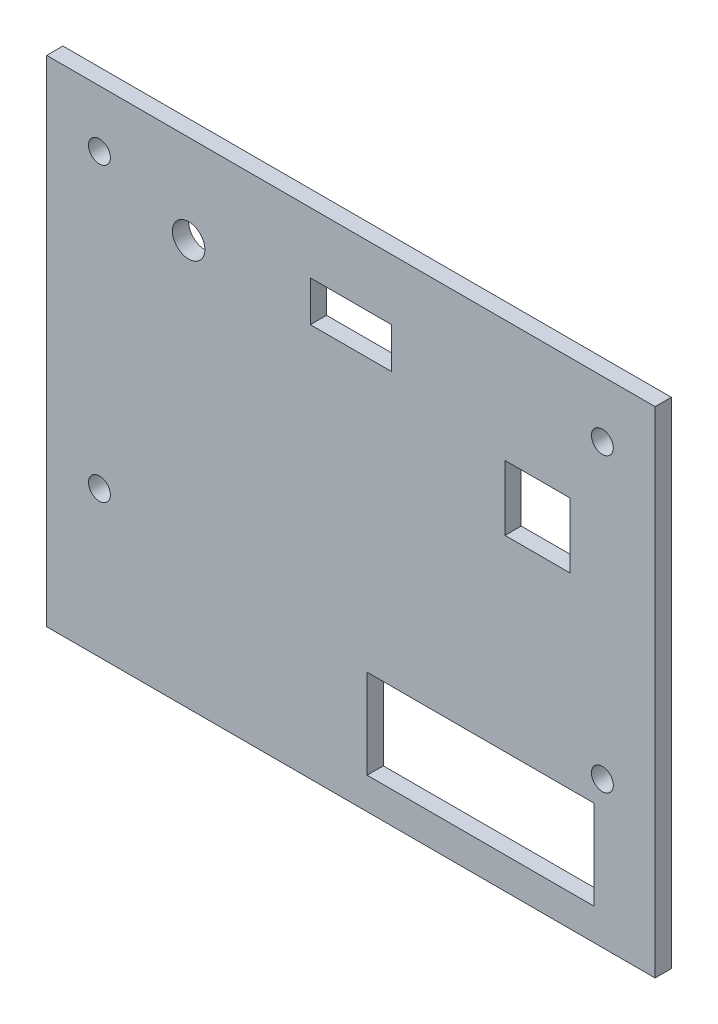
SolidWorks part; units mm, degrees
ref_plane "前视基准面" through (0, 0, 0) normal (0, 0, 1) x (1, 0, 0)
ref_plane "上视基准面" through (0, 0, 0) normal (0, 1, 0) x (1, 0, 0)
ref_plane "右视基准面" through (0, 0, 0) normal (1, 0, 0) x (0, 0, -1)
other "Configuration Table"
sketch "草图1" plane through (0, 0, 0) normal (0, 0, 1) x (1, 0, 0)
  line L1 (0, 0) -> (75, 0)
  line L2 (0, 0) -> (0, 61)
  line L3 (0, 61) -> (75, 61)
  line L4 (75, 0) -> (75, 61)
extrude "凸台-拉伸1" add sketch "草图1" along normal blind 2
sketch "草图2" plane through (0, 0, 0) normal (0, 0, 1) x (1, 0, 0)
  line L1 (39.5, 3.9) -> (67.5, 3.9)
  line L2 (39.5, 3.9) -> (39.5, 14.9)
  line L3 (39.5, 14.9) -> (67.5, 14.9)
  line L4 (67.5, 3.9) -> (67.5, 14.9)
extrude "切除-拉伸1" cut sketch "草图2" along normal through all
sketch "草图3" plane through (0, 0, 0) normal (0, 0, 1) x (1, 0, 0)
  line L1 (32.5, 48.5) -> (42.5, 48.5)
  line L2 (32.5, 48.5) -> (32.5, 53.5)
  line L3 (32.5, 53.5) -> (42.5, 53.5)
  line L4 (42.5, 48.5) -> (42.5, 53.5)
  line L5 (56.5, 38) -> (64.5, 38)
  line L6 (56.5, 38) -> (56.5, 46)
  line L7 (56.5, 46) -> (64.5, 46)
  line L8 (64.5, 38) -> (64.5, 46)
extrude "切除-拉伸2" cut sketch "草图3" along normal through all
sketch "草图4" plane through (0, 0, 0) normal (0, 0, 1) x (1, 0, 0)
  circle A0 centre (6.5, 18) radius 1.35
  circle A1 centre (68.5, 18) radius 1.35
  circle A2 centre (6.5, 54) radius 1.35
  circle A3 centre (68.5, 54) radius 1.35
extrude "切除-拉伸3" cut sketch "草图4" along normal through all
sketch "草图5" plane through (0, 0, 0) normal (0, 0, 1) x (1, 0, 0)
  circle A0 centre (17.5, 50) radius 2
extrude "切除-拉伸4" cut sketch "草图5" along normal through all
